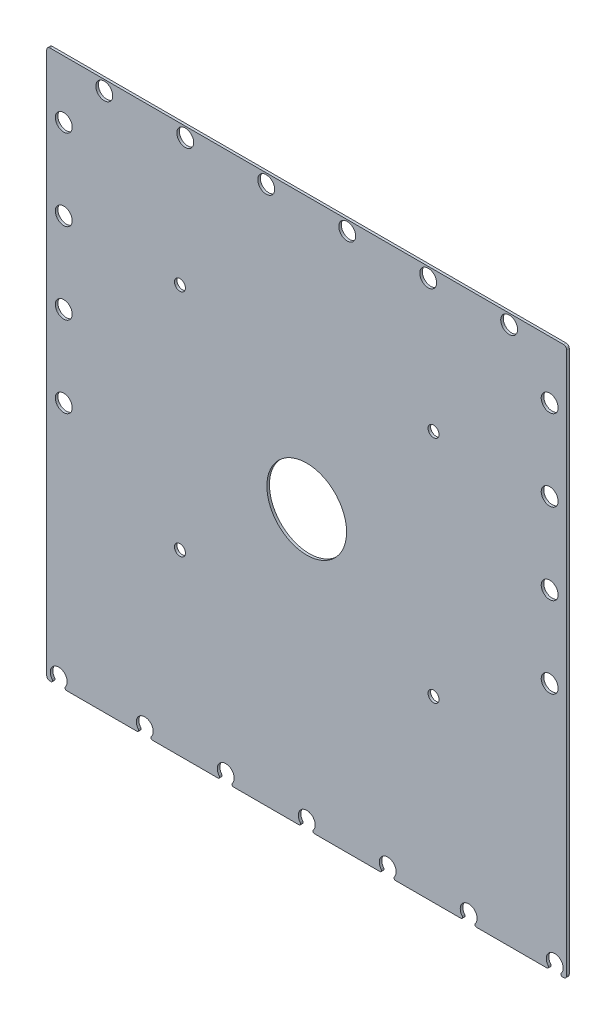
SolidWorks part; units mm, degrees
material "6061 Alloy"
ref_plane "Front Plane" through (0, 0, 0) normal (0, 0, 1) x (1, 0, 0)
ref_plane "Top Plane" through (0, 0, 0) normal (0, 1, 0) x (1, 0, 0)
ref_plane "Right Plane" through (0, 0, 0) normal (1, 0, 0) x (0, 0, -1)
sketch "Sketch2" plane through (0, 0, 0) normal (0, 0, 1) x (1, 0, 0)
  line L0 (0, -176.7623) -> (165.1, -176.7623)
  line L1 (0, 0) -> (165.1, 0)
  line L5 (82.55, 0) -> (82.55, -176.7623) construction
  line L6 (165.1, 0) -> (165.1, -176.7623)
  line L7 (0, 0) -> (0, -176.7623)
  line L8 (0, 0) -> (0, -176.7623)
  line L9 (0, -171.98) -> (165.1, -171.98)
  line L10 (1, 0) -> (1, -171.98)
  line L11 (164.1, -171.98) -> (164.1, 0)
  line L12 (1, -166.6) -> (164.1, -166.6)
  circle A31 centre (31.75, -169.48) radius 2.65
  circle A32 centre (57.15, -169.48) radius 2.65
  circle A33 centre (82.55, -169.48) radius 2.65
  circle A34 centre (107.95, -169.48) radius 2.65
  circle A35 centre (133.35, -169.48) radius 2.65
  circle A63 centre (6.35, -18.05) radius 2.65
  circle A65 centre (160.3375, -169.48) radius 2.65
  circle A66 centre (4.7625, -169.48) radius 2.65
  circle A67 centre (82.55, -85) radius 12.5
  circle A69 centre (19.05, -3.175) radius 2.65
  circle A70 centre (44.45, -3.175) radius 2.65
  circle A71 centre (69.85, -3.175) radius 2.65
  circle A72 centre (95.25, -3.175) radius 2.65
  circle A73 centre (120.65, -3.175) radius 2.65
  circle A74 centre (146.05, -3.175) radius 2.65
  circle A76 centre (6.35, -43.45) radius 2.65
  circle A77 centre (6.35, -68.85) radius 2.65
  circle A78 centre (6.35, -94.25) radius 2.65
  circle A81 centre (158.75, -68.85) radius 2.65
  circle A82 centre (158.75, -94.25) radius 2.65
  circle A83 centre (158.75, -43.45) radius 2.65
  circle A84 centre (158.75, -18.05) radius 2.65
  dimension "D9" = 5.3
  dimension "D4" = 5.3
  dimension "D21" = 25
  dimension "D1" = 165.1
  dimension "D23" = 25.4
  dimension "D5" = 176.7623
  dimension "D8" = 31.75
  dimension "D11" = 7.2823
  dimension "D10" = 19.05
  dimension "D12" = 3.175
  dimension "D14" = 25.4
  dimension "D3" = 18.05
  dimension "D6" = 6.35
  dimension "D15" = 25.4
  dimension "D16" = 2.5
  dimension "D17" = 4.7625
  dimension "D18" = 1
  dimension "D19" = 1
  dimension "D20" = 85
  dimension "D24" = 5.38
  dimension "D22" = 5
  dimension "D13" = 3
  dimension "D7" = 4
extrude "Boss-Extrude2" add sketch "Sketch2" along normal blind 0.8
fillet "Fillet1" radius 1 4 edges at (1, -171.98, 0.4) (1, 0, 0.4) (164.1, 0, 0.4) (164.1, -171.98, 0.4)
sketch "Sketch5" plane through (0, 0, 0.8) normal (0, 0, 1) x (1, 0, 0)
  line L0 (122.325, -43.995) -> (122.325, -115.985) construction
  line L1 (42.775, -43.995) -> (122.325, -43.995) construction
  line L7 (42.775, -43.995) -> (42.775, -115.985) construction
  line L9 (42.775, -115.985) -> (122.325, -115.985) construction
  line L10 (2, 0) -> (2, -171.98) construction
  line L11 (1, -1) -> (164.1, -1) construction
  circle A0 centre (82.55, -85) radius 12.5 construction
  circle A1 centre (42.775, -43.995) radius 1.725
  circle A2 centre (122.325, -43.995) radius 1.725
  circle A3 centre (122.325, -115.985) radius 1.725
  circle A4 centre (42.775, -115.985) radius 1.725
  point P4 (82.55, -85)
  point P11 (0, 0)
  point P15 (82.55, -43.995)
  point P30 (0, 0)
  point P31 (1, -171.98)
  dimension "D3" = 3.45
  dimension "D1" = 163.1
  dimension "D2" = 171.98
  dimension "D4" = 42.995
  dimension "D5" = 40.775
  dimension "D6" = 55.995
  dimension "D7" = 115.985
  dimension "D8" = 171.98
extrude "Cut-Extrude1" cut sketch "Sketch5" against normal through all both and the other way through all
fillet "Fillet2" radius 0.5 14 edges at (161.2164, -171.98, 0.4) (159.4586, -171.98, 0.4) (134.2289, -171.98, 0.4) (132.4711, -171.98, 0.4) (108.8289, -171.98, 0.4) (107.0711, -171.98, 0.4) (83.4289, -171.98, 0.4) (81.6711, -171.98, 0.4) (58.0289, -171.98, 0.4) (56.2711, -171.98, 0.4) (32.6289, -171.98, 0.4) (30.8711, -171.98, 0.4) (5.6414, -171.98, 0.4) (3.8836, -171.98, 0.4)
equation "\"D19@Sketch2\"=\"D18@Sketch2\""
equation "\"D9@Sketch2\"=\"D4@Sketch2\""
equation "\"D4@Sketch5\"=\"D2@Sketch5\"/4"
equation "\"D5@Sketch5\"=\"D1@Sketch5\"/4"
